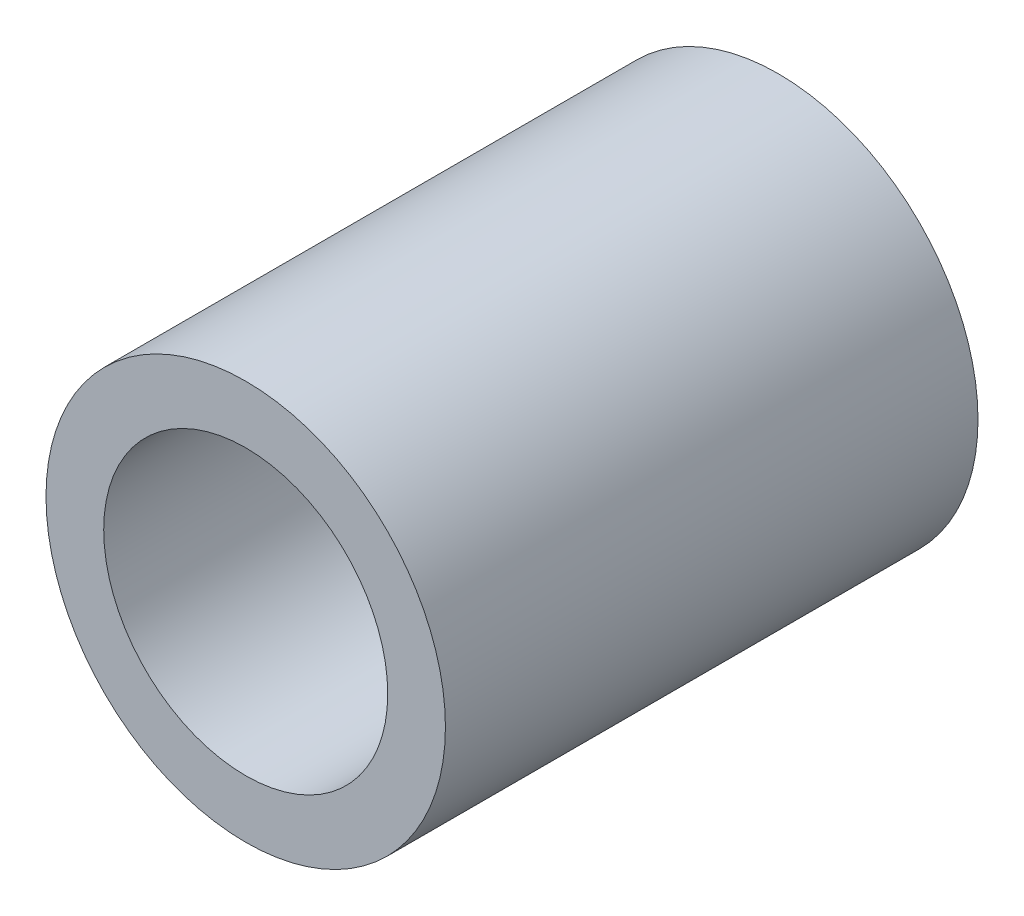
SolidWorks part; units mm, degrees
ref_plane "Front Plane" through (0, 0, 0) normal (0, 0, 1) x (1, 0, 0)
ref_plane "Top Plane" through (0, 0, 0) normal (0, 1, 0) x (1, 0, 0)
ref_plane "Right Plane" through (0, 0, 0) normal (1, 0, 0) x (0, 0, -1)
sketch "Sketch1" plane through (0, 0, 0) normal (0, 0, 1) x (1, 0, 0)
  circle A0 centre (0, 0) radius 2.25
  circle A1 centre (0, 0) radius 1.6
  dimension "OD" = 4.5
  dimension "ID" = 3.2
extrude "Extrude1" add sketch "Sketch1" along normal mid plane 6
sketch "Sketch2" plane through (0, 0, 0) normal (1, 0, 0) x (0, 0, -1)
  line L0 (-3, -1.6) -> (3, -1.6) construction
  line L3 (3, 1.6) -> (-3, 1.6) construction
  line L5 (-3, -1.6) -> (3, -1.6)
  line L6 (3, 1.6) -> (-3, 1.6)
sketch "Sketch4" plane through (0, 0, 3) normal (0, 0, 1) x (1, 0, 0)
  line L0 (0, 0) -> (-1.1314, 1.1314)
  line L1 (0, -2.2) -> (0, 2.2) construction
  circle A0 centre (0, 0) radius 1.6 construction
  dimension "D1" = 45
